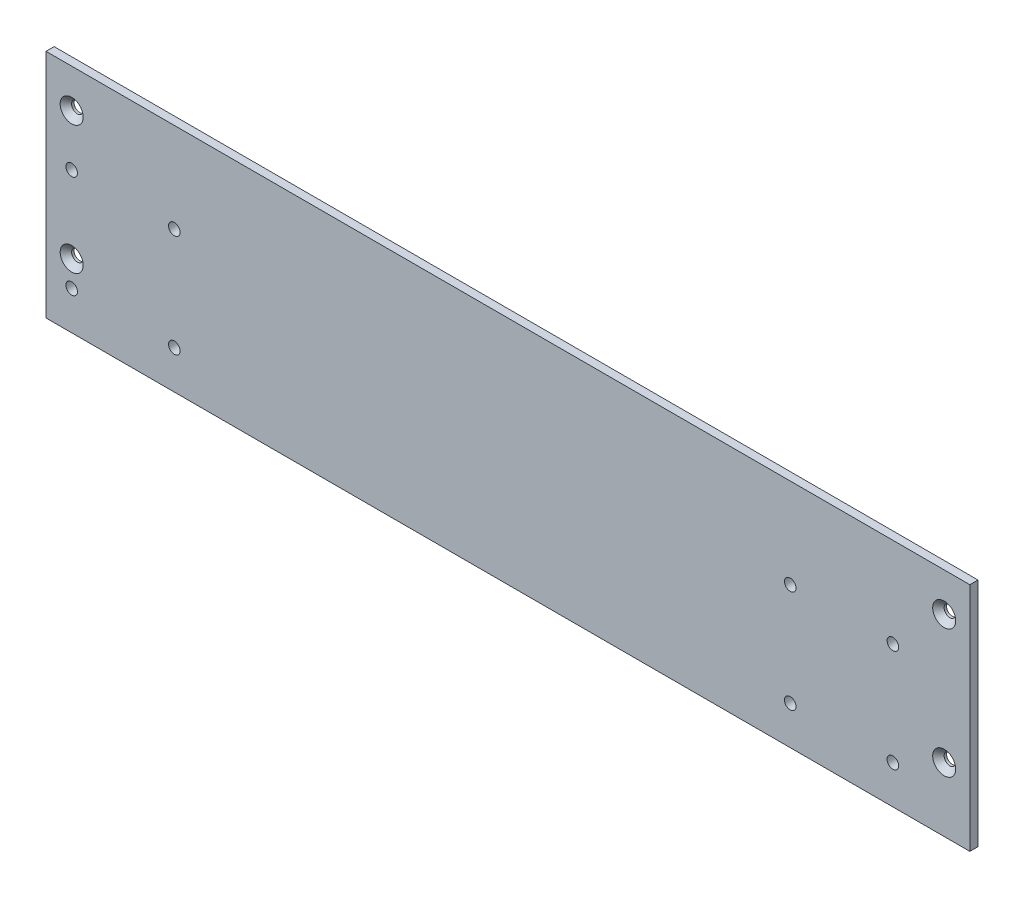
SolidWorks part; units mm, degrees
ref_plane "Front Plane" through (0, 0, 0) normal (0, 0, 1) x (1, 0, 0)
ref_plane "Top Plane" through (0, 0, 0) normal (0, 1, 0) x (1, 0, 0)
ref_plane "Right Plane" through (0, 0, 0) normal (1, 0, 0) x (0, 0, -1)
sketch "Sketch1" plane through (0, 0, 0) normal (0, 0, 1) x (1, 0, 0)
  line L1 (-180, -45) -> (180, -45)
  line L2 (-180, -45) -> (-180, 45)
  line L3 (-180, 45) -> (180, 45)
  line L4 (180, -45) -> (180, 45)
  line L5 (-180, -45) -> (180, 45) construction
  line L6 (-180, 45) -> (180, -45) construction
  point P0 (0, 0)
  dimension "D1" = 360
  dimension "D2" = 90
extrude "Boss-Extrude1" add sketch "Sketch1" along normal blind 3.175
hole_wizard "M4 Clearance Hole1" positions "Sketch2" profile "Sketch4" hole size "M4" standard "ANSI Metric" end condition through all
sketch "Sketch2" plane through (0, 0, 3.175) normal (0, 0, 1) x (1, 0, 0)
  line L1 (-170, -30) -> (-130, -30)
  line L2 (-170, -30) -> (-170, 10)
  line L3 (-170, 10) -> (-130, 10)
  line L4 (-130, -30) -> (-130, 10)
  line L5 (-170, -30) -> (-130, 10) construction
  line L6 (-170, 10) -> (-130, -30) construction
  line L7 (-180, 45) -> (-180, -45) construction
  line L8 (110, -30) -> (150, -30)
  line L9 (110, -30) -> (110, 10)
  line L10 (110, 10) -> (150, 10)
  line L11 (150, -30) -> (150, 10)
  line L12 (110, -30) -> (150, 10) construction
  line L13 (110, 10) -> (150, -30) construction
  line L14 (-180, -45) -> (180, -45) construction
  line L15 (180, -45) -> (180, 45) construction
  point P1 (-130, 10)
  point P48 (-170, -30)
  point P49 (-170, 10)
  point P50 (-130, -30)
  point P53 (-150, -10)
  point P66 (110, 10)
  point P69 (150, 10)
  point P72 (150, -30)
  point P75 (110, -30)
  point P81 (130, -10)
  dimension "D1" = 40
  dimension "D2" = 40
  dimension "D3" = 30
  dimension "D5" = 35
  dimension "D6" = 50
  dimension "D4" = 2
sketch "Sketch4" plane through (-130, 10, 3.175) normal (1, 0, 0) x (0, -1, 0)
  line L0 (0, 0) -> (0, 3.175)
  line L1 (0, 3.175) -> (2.25, 3.175)
  line L2 (2.25, 3.175) -> (2.25, 0)
  line L5 (2.25, 0) -> (0, 0)
  line L11 (0, -6.35) -> (0, 107.95) construction
  dimension "Thru Hole Dia." = 4.5
  dimension "Thru Hole Depth" = 3.175
hole_wizard "CSK for M4 SFHCS1" positions "Sketch5" profile "Sketch7" countersink size "M4" standard "ANSI Metric" end condition through all
sketch "Sketch5" plane through (0, 0, 3.175) normal (0, 0, 1) x (1, 0, 0)
  line L1 (-170, -20) -> (170, -20)
  line L2 (-170, -20) -> (-170, 30)
  line L3 (-170, 30) -> (170, 30)
  line L4 (170, -20) -> (170, 30)
  line L5 (-170, -20) -> (170, 30) construction
  line L6 (-170, 30) -> (170, -20) construction
  line L7 (-180, 45) -> (-180, -45) construction
  line L8 (180, -45) -> (180, 45) construction
  line L9 (-180, -45) -> (180, -45) construction
  point P2 (170, 30)
  point P67 (-170, -20)
  point P68 (-170, 30)
  point P69 (170, -20)
  dimension "D1" = 50
  dimension "D2" = 10
  dimension "D3" = 10
  dimension "D4" = 25
sketch "Sketch7" plane through (170, 30, 3.175) normal (1, 0, 0) x (0, -1, 0)
  line L0 (0, 0) -> (0, 3.175)
  line L1 (0, 3.175) -> (2.25, 3.175)
  line L2 (2.25, 3.175) -> (2.25, 2.23)
  line L3 (2.25, 2.23) -> (4.48, 0)
  line L5 (4.48, 0) -> (0, 0)
  line L6 (-2.25, 2.23) -> (-4.48, 0) construction
  line L11 (0, -6.35) -> (0, 107.95) construction
  dimension "Thru Hole Dia." = 4.5
  dimension "Thru Hole Depth" = 3.175
  dimension "Near C'Sink Dia." = 8.96
  dimension "Near C'Sink Angle" = 90
